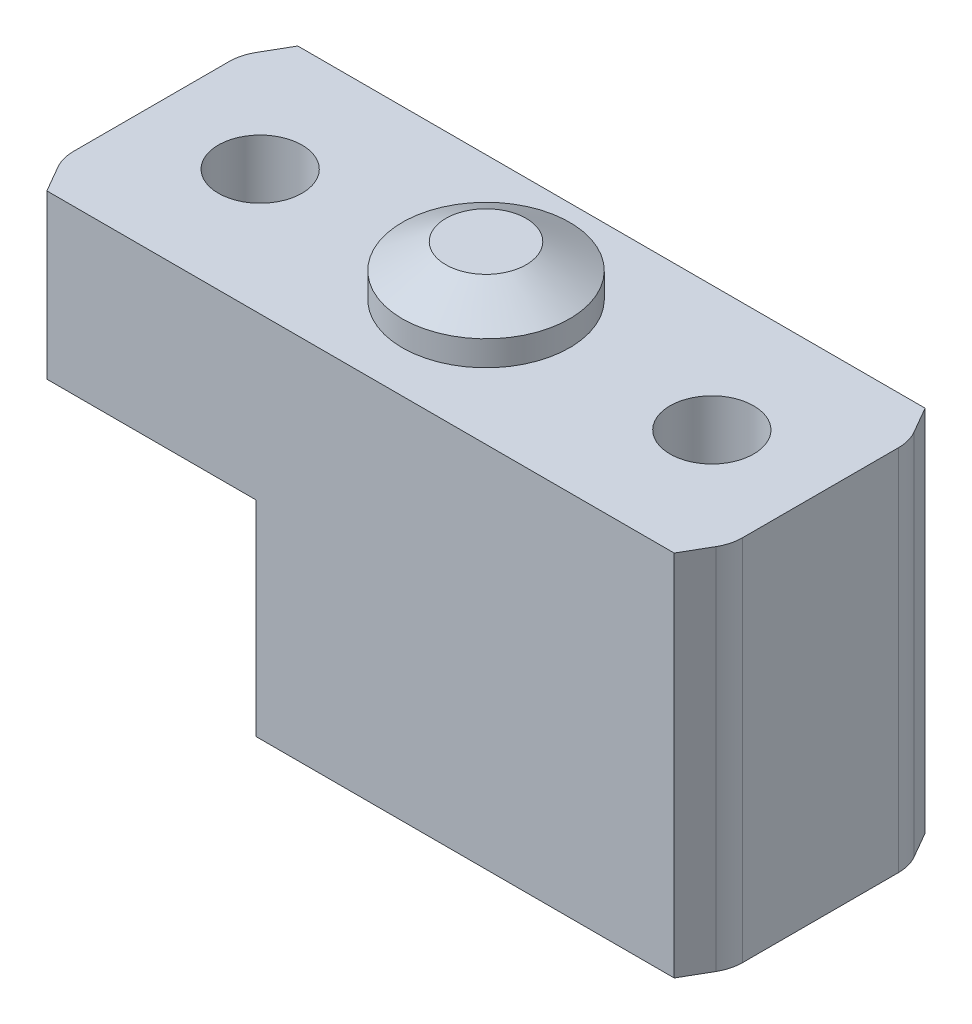
SolidWorks part; units mm, degrees
ref_plane "Front Plane" through (0, 0, 0) normal (0, 0, 1) x (1, 0, 0)
ref_plane "Top Plane" through (0, 0, 0) normal (0, 1, 0) x (1, 0, 0)
ref_plane "Right Plane" through (0, 0, 0) normal (1, 0, 0) x (0, 0, -1)
sketch "Sketch1" plane through (0, 0, 0) normal (0, 1, 0) x (1, 0, 0)
  line L1 (0, 0) -> (8, 0)
  line L2 (0, 0) -> (0, -3)
  line L3 (0, -3) -> (8, -3)
  line L4 (8, 0) -> (8, -3)
  dimension "D1" = 3
  dimension "D2" = 8
extrude "Boss-Extrude1" add sketch "Sketch1" along normal blind 2.2
sketch "Sketch2" plane through (0, 2.2, 0) normal (0, 1, 0) x (1, 0, 0)
  line L0 (8, 0) -> (0, 0) construction
  line L1 (4, 0) -> (4, -3) construction
  line L2 (0, -3) -> (8, -3) construction
  circle A0 centre (4, -1.5) radius 1
  dimension "D1" = 2
extrude "Boss-Extrude2" add sketch "Sketch2" along normal blind 0.6
sketch "Sketch3" plane through (0, 2.2, 0) normal (0, 1, 0) x (1, 0, 0)
  line L0 (0, -1.5) -> (8, -1.5) construction
  line L1 (0, 0) -> (0, -3) construction
  line L2 (8, -3) -> (8, 0) construction
  line L3 (4, -1.5) -> (4, 0) construction
  line L4 (8, 0) -> (0, 0) construction
  circle A0 centre (1.3, -1.5) radius 0.5
  circle A1 centre (6.7, -1.5) radius 0.5
  dimension "D1" = 1
  dimension "D2" = 2.7
extrude "Cut-Extrude1" cut sketch "Sketch3" against normal blind 2.5
sketch "Sketch4" plane through (0, 0, 0) normal (0, -1, 0) x (1, 0, 0)
  line L0 (8, 0) -> (0, 0) construction
  line L1 (8, 3) -> (2.5, 3)
  line L2 (8, 3) -> (8, 0)
  line L3 (8, 0) -> (2.5, 0)
  line L4 (2.5, 3) -> (2.5, 0)
  circle A0 centre (4, 1.5) radius 1 construction
  dimension "D1" = 1.5
extrude "Boss-Extrude3" add sketch "Sketch4" along normal blind 2.2
sketch "Sketch5" plane through (0, -2.2, 0) normal (0, -1, 0) x (1, 0, 0)
  circle A0 centre (4, 1.5) radius 1
extrude "Boss-Extrude4" add sketch "Sketch5" along normal blind 0.6
sketch "Sketch6" plane through (0, -2.2, 0) normal (0, -1, 0) x (1, 0, 0)
  circle A0 centre (6.7, 1.5) radius 0.5
extrude "Cut-Extrude2" cut sketch "Sketch6" against normal blind 2.5
chamfer "Chamfer1" distance 0.25 angle 60 8 edges at (8, 0, 0) (2.5, -1.1, 0) (1.25, 0, 0) (0, 1.1, 0) (0, 1.1, 3) (1.25, 0, 3) (2.5, -1.1, 3) (8, 0, 3)
fillet "Fillet1" radius 0.5 8 edges at (2.5, -1.1, 2.567) (1.25, 0, 2.567) (0, 1.1, 2.567) (0, 1.1, 0.433) (1.25, 0, 0.433) (2.5, -1.1, 0.433) (8, 0, 2.567) (8, 0, 0.433)
chamfer "Chamfer2" distance 0.3 angle 60 2 edges at (4, -2.8, 0.5) (4, 2.8, 2.5)
